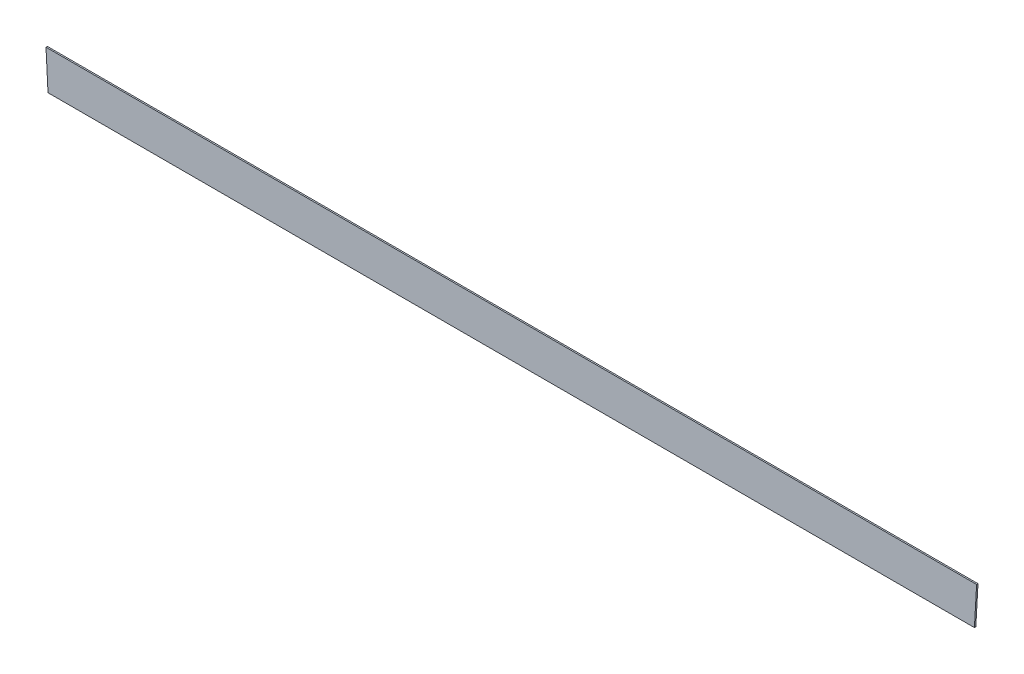
SolidWorks part; units mm, degrees
ref_plane "Front Plane" through (0, 0, 0) normal (0, 0, 1) x (1, 0, 0)
ref_plane "Top Plane" through (0, 0, 0) normal (0, 1, 0) x (1, 0, 0)
ref_plane "Right Plane" through (0, 0, 0) normal (1, 0, 0) x (0, 0, -1)
sketch "Sketch1" plane through (0, 0, 0) normal (0, 0, 1) x (1, 0, 0)
  line L0 (-662.5, 27.5) -> (-665.3824, 27.5)
  line L1 (-662.5, -27.5) -> (662.5, -27.5)
  line L2 (-662.5, -27.5) -> (-662.5, 27.5) construction
  line L3 (-662.5, 27.5) -> (662.5, 27.5)
  line L4 (662.5, -27.5) -> (662.5, 27.5) construction
  line L5 (-662.5, -27.5) -> (662.5, 27.5) construction
  line L6 (-662.5, 27.5) -> (662.5, -27.5) construction
  line L7 (-665.3824, 27.5) -> (-662.5, -27.5)
  line L8 (662.5, 27.5) -> (665.6176, 27.5)
  line L9 (665.6176, 27.5) -> (662.5, -27.5)
  point P0 (0, 0)
  dimension "D1" = 1325
  dimension "D2" = 55
  dimension "D3" = 1331
extrude "Boss-Extrude1" add sketch "Sketch1" along normal blind 2
